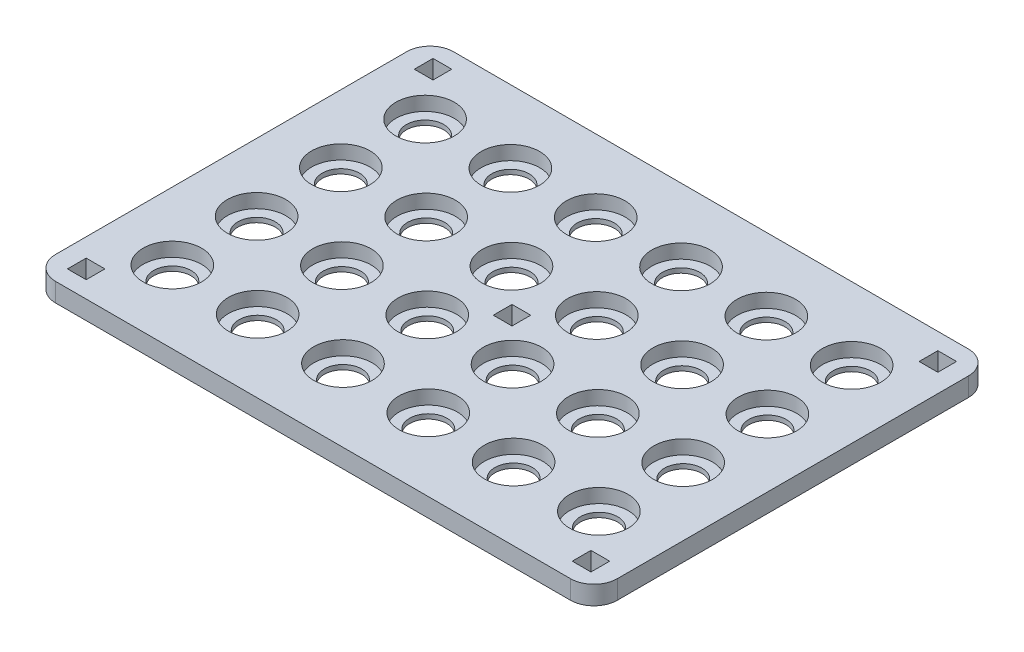
SolidWorks part; units mm, degrees
ref_plane "Front Plane" through (0, 0, 0) normal (0, 0, 1) x (1, 0, 0)
ref_plane "Top Plane" through (0, 0, 0) normal (0, 1, 0) x (1, 0, 0)
ref_plane "Right Plane" through (0, 0, 0) normal (1, 0, 0) x (0, 0, -1)
sketch "Sketch1" plane through (0, 0, 0) normal (0, 1, 0) x (1, 0, 0)
  line L1 (-60, 42.5) -> (60, 42.5)
  line L2 (-60, 42.5) -> (-60, -42.5)
  line L3 (-60, -42.5) -> (60, -42.5)
  line L4 (60, 42.5) -> (60, -42.5)
  line L5 (-60, 42.5) -> (60, -42.5) construction
  line L6 (-60, -42.5) -> (60, 42.5) construction
  point P0 (0, 0)
  dimension "D1" = 120
  dimension "D2" = 85
extrude "Boss-Extrude1" add sketch "Sketch1" along normal mid plane 35
sketch "Sketch2" plane through (0, 17.5, 0) normal (0, 1, 0) x (1, 0, 0)
  line L0 (-45.5658, 27) -> (-60, 27) construction
  line L1 (-60, 42.5) -> (-60, -42.5) construction
  line L2 (-45.5658, 27) -> (-45.5658, 42.5) construction
  line L3 (60, 42.5) -> (-60, 42.5) construction
  line L4 (45.5658, -27) -> (60, -27) construction
  line L5 (60, -42.5) -> (60, 42.5) construction
  line L6 (45.5658, -27) -> (45.5658, -42.5) construction
  line L7 (-60, -42.5) -> (60, -42.5) construction
  circle A0 centre (-45.5658, 27) radius 6.25
  circle A1 centre (-27.3395, 27) radius 6.25
  circle A2 centre (-9.1132, 27) radius 6.25
  circle A3 centre (9.1131, 27) radius 6.25
  circle A4 centre (27.3394, 27) radius 6.25
  circle A5 centre (45.5657, 27) radius 6.25
  circle A6 centre (-27.3395, 9) radius 6.25
  circle A7 centre (-9.1132, 9) radius 6.25
  circle A8 centre (9.1131, 9) radius 6.25
  circle A9 centre (27.3394, 9) radius 6.25
  circle A10 centre (45.5657, 9) radius 6.25
  circle A11 centre (-27.3394, -9) radius 6.25
  circle A12 centre (-9.1131, -9) radius 6.25
  circle A13 centre (9.1132, -9) radius 6.25
  circle A14 centre (27.3395, -9) radius 6.25
  circle A15 centre (45.5658, -9) radius 6.25
  circle A16 centre (-27.3394, -27) radius 6.25
  circle A17 centre (-9.1131, -27) radius 6.25
  circle A18 centre (9.1132, -27) radius 6.25
  circle A19 centre (27.3395, -27) radius 6.25
  circle A20 centre (45.5658, -27) radius 6.25
  circle A21 centre (-45.5658, 9) radius 6.25
  circle A22 centre (-45.5657, -9) radius 6.25
  circle A23 centre (-45.5657, -27) radius 6.25
  dimension "D3" = 12.5
  dimension "D4" = 18.2263
  dimension "D1" = 6
  dimension "D2" = 4
extrude "Cut-Extrude1" cut sketch "Sketch2" against normal blind 34
sketch "Sketch5" plane through (0, 17.5, 0) normal (0, 1, 0) x (1, 0, 0)
  circle A0 centre (-45.5658, 27) radius 4
  circle A1 centre (-27.3361, 27) radius 4
  circle A2 centre (-9.1064, 27) radius 4
  circle A3 centre (9.1233, 27) radius 4
  circle A4 centre (27.353, 27) radius 4
  circle A5 centre (45.5827, 27) radius 4
  circle A6 centre (-27.3361, 9) radius 4
  circle A7 centre (-9.1064, 9) radius 4
  circle A8 centre (9.1233, 9) radius 4
  circle A9 centre (27.353, 9) radius 4
  circle A10 centre (45.5827, 9) radius 4
  circle A11 centre (-27.3361, -9) radius 4
  circle A12 centre (-9.1064, -9) radius 4
  circle A13 centre (9.1233, -9) radius 4
  circle A14 centre (27.353, -9) radius 4
  circle A15 centre (45.5827, -9) radius 4
  circle A16 centre (-27.3361, -27) radius 4
  circle A17 centre (-9.1064, -27) radius 4
  circle A18 centre (9.1233, -27) radius 4
  circle A19 centre (27.353, -27) radius 4
  circle A20 centre (45.5827, -27) radius 4
  circle A21 centre (-45.5658, 9) radius 4
  circle A22 centre (-45.5657, -9) radius 4
  circle A23 centre (-45.5657, -27) radius 4
  dimension "D1" = 8
  dimension "D4" = 18.2297
  dimension "D2" = 6
  dimension "D3" = 4
extrude "Cut-Extrude4" cut sketch "Sketch5" against normal through all
fillet "Fillet1" radius 5 4 edges at (60, 0, -42.5) (60, 0, 42.5) (-60, 0, 42.5) (-60, 0, -42.5)
sketch "Sketch3" plane through (0, 0, -42.5) normal (0, 0, -1) x (-1, 0, 0)
  line L0 (-52.1057, 13.5) -> (-52.1057, 17.5) construction
  line L1 (52.1057, 13.5) -> (-52.1057, 13.5)
  line L2 (52.1057, 13.5) -> (52.1057, -13.5)
  line L3 (52.1057, -13.5) -> (-52.1057, -13.5)
  line L4 (-52.1057, 13.5) -> (-52.1057, -13.5)
  line L5 (-55, 17.5) -> (55, 17.5) construction
  line L6 (52.1057, -13.5) -> (52.1057, -17.5) construction
  line L7 (-55, -17.5) -> (55, -17.5) construction
  line L8 (-52.1057, 13.5) -> (-55, 13.5) construction
  line L11 (-55, 17.5) -> (-55, -17.5) construction
  line L13 (52.1057, -13.5) -> (55, -13.5) construction
  line L14 (55, -17.5) -> (55, 17.5) construction
  dimension "D1" = 27
extrude "Cut-Extrude2" cut sketch "Sketch3" against normal through all
sketch "Sketch4" plane through (60, 0, 0) normal (1, 0, 0) x (0, 0, -1)
  line L0 (-34.7795, 13.5) -> (-34.7795, 17.5) construction
  line L1 (34.7795, 13.5) -> (-34.7795, 13.5)
  line L2 (34.7795, 13.5) -> (34.7795, -13.5)
  line L3 (34.7795, -13.5) -> (-34.7795, -13.5)
  line L4 (-34.7795, 13.5) -> (-34.7795, -13.5)
  line L5 (-37.5, 17.5) -> (37.5, 17.5) construction
  line L6 (34.7795, 13.5) -> (37.5, 13.5) construction
  line L7 (-34.7795, 13.5) -> (-37.5, 13.5) construction
  line L8 (34.7795, -13.5) -> (34.7795, -17.5) construction
  line L9 (-37.5, -17.5) -> (37.5, -17.5) construction
  line L10 (34.7795, -13.5) -> (37.5, -13.5) construction
  line L11 (37.5, -17.5) -> (37.5, 17.5) construction
  line L12 (-37.5, 17.5) -> (-37.5, -17.5) construction
  dimension "D1" = 27
extrude "Cut-Extrude3" cut sketch "Sketch4" against normal through all
sketch "Sketch6" plane through (0, 17.5, 0) normal (0, 1, 0) x (1, 0, 0)
  line L1 (-2, 2) -> (2, 2)
  line L2 (-2, 2) -> (-2, -2)
  line L3 (-2, -2) -> (2, -2)
  line L4 (2, 2) -> (2, -2)
  line L5 (-2, 2) -> (2, -2) construction
  line L6 (-2, -2) -> (2, 2) construction
  point P0 (0, 0)
  dimension "D1" = 4
extrude "Boss-Extrude2" add sketch "Sketch6" against normal up to surface (35 mm away) up to face at (-45.5657, -17.5, 31)
chamfer "Chamfer1" distance 1 angle 45 8 edges at (0, -13.5, 2) (-2, -13.5, 0) (2, -13.5, 0) (0, -13.5, -2) (0, 13.5, 2) (-2, 13.5, 0) (2, 13.5, 0) (0, 13.5, -2)
sketch "Sketch7" plane through (0, 17.5, 0) normal (0, 1, 0) x (1, 0, 0)
  line L0 (-45.5658, 27) -> (-27.3361, 27) construction
  line L1 (-27.3361, 27) -> (-9.1064, 27) construction
  line L2 (-9.1064, 27) -> (9.1233, 27) construction
  line L3 (9.1233, 27) -> (27.353, 27) construction
  line L4 (27.353, 27) -> (45.5827, 27) construction
  line L5 (45.5827, 27) -> (45.5827, 9) construction
  line L6 (45.5827, 9) -> (45.5827, -9) construction
  line L7 (45.5827, -9) -> (45.5827, -27) construction
  line L8 (45.5827, -27) -> (27.353, -27) construction
  line L9 (27.353, -27) -> (9.1233, -27) construction
  line L10 (9.1233, -27) -> (-9.1064, -27) construction
  line L11 (-9.1064, -27) -> (-27.3361, -27) construction
  line L12 (-27.3361, -27) -> (-45.5657, -27) construction
  line L13 (-45.5657, -27) -> (-45.5657, -9) construction
  line L14 (-45.5657, -9) -> (-45.5658, 9) construction
  line L15 (-45.5658, 9) -> (-45.5658, 27) construction
  line L16 (-27.3361, 27) -> (-27.3361, 9) construction
  line L17 (-27.3361, 9) -> (-27.3361, -9) construction
  line L18 (-27.3361, -9) -> (-27.3361, -27) construction
  line L19 (-9.1064, 27) -> (-9.1064, 9) construction
  line L20 (-9.1064, 9) -> (-9.1064, -9) construction
  line L21 (-9.1064, -9) -> (-9.1064, -27) construction
  line L22 (9.1233, 27) -> (9.1233, 9) construction
  line L23 (9.1233, 9) -> (9.1233, -9) construction
  line L24 (9.1233, -9) -> (9.1233, -27) construction
  line L25 (27.353, 27) -> (27.353, 9) construction
  line L26 (27.353, 9) -> (27.353, -9) construction
  line L27 (27.353, -9) -> (27.353, -27) construction
  line L28 (-45.5658, 9) -> (-27.3361, 9) construction
  line L29 (-27.3361, 9) -> (-9.1064, 9) construction
  line L30 (-9.1064, 9) -> (9.1233, 9) construction
  line L31 (9.1233, 9) -> (27.353, 9) construction
  line L32 (27.353, 9) -> (45.5827, 9) construction
  line L33 (-45.5657, -9) -> (-27.3361, -9) construction
  line L34 (-27.3361, -9) -> (-9.1064, -9) construction
  line L35 (-9.1064, -9) -> (9.1233, -9) construction
  line L36 (9.1233, -9) -> (27.353, -9) construction
  line L37 (27.353, -9) -> (45.5827, -9) construction
  line L38 (-45.5657, -27) -> (-45.5657, -36) construction
  line L39 (-45.5657, -36) -> (45.5827, -36) construction
  line L40 (45.5827, -36) -> (45.5827, -27) construction
  text T0 "A1"
  text T1 "A2"
  text T2 "A3"
  text T3 "A4"
  text T4 "A5"
  text T5 "A6"
  text T6 "B1"
  text T7 "B2"
  text T8 "B3"
  text T9 "B4"
  text T10 "B5"
  text T11 "B6"
  text T12 "C1"
  text T13 "C2"
  text T14 "C3"
  text T15 "C4"
  text T16 "C5"
  text T17 "C6"
  text T18 "D1"
  text T19 "D2"
  text T20 "D3"
  text T21 "D4"
  text T22 "D5"
  text T23 "D6"
  point P24 (-28.1815, -36)
  point P26 (-9.388, -36)
  point P28 (9.4055, -36)
  point P31 (28.199, -36)
  point P64 (-45.5657, 18)
  point P65 (-36.4509, 27)
  point P66 (-27.3361, 18)
  point P67 (-18.2212, 27)
  point P68 (-9.1064, 18)
  point P69 (0.0085, 27)
  point P70 (9.1233, 18)
  point P71 (18.2382, 27)
  point P72 (36.4679, 27)
  point P73 (45.5827, 18)
  point P74 (27.353, 18)
  point P75 (-36.4509, 9)
  point P76 (-45.5657, 0)
  point P77 (-27.3361, 0)
  point P78 (-9.1064, 0)
  point P79 (9.1233, 0)
  point P80 (27.353, 0)
  point P81 (45.5827, 0)
  point P82 (36.4679, 9)
  point P83 (18.2382, 9)
  point P84 (0.0085, 9)
  point P85 (-18.2212, 9)
  point P86 (-36.4509, -9)
  point P87 (-36.4509, -27)
  point P88 (-18.2212, -27)
  point P89 (0.0085, -27)
  point P90 (18.2382, -27)
  point P91 (36.4679, -27)
  point P92 (36.4679, -9)
  point P93 (45.5827, -18)
  point P94 (27.353, -18)
  point P95 (9.1233, -18)
  point P96 (-9.1064, -18)
  point P97 (-27.3361, -18)
  point P98 (-45.5657, -18)
  dimension "D1" = 9
extrude "Cut-Extrude5" [suppressed] cut sketch "Sketch7" against normal blind 1
chamfer "Chamfer2" [suppressed] distance 1 angle 45
chamfer "Chamfer3" distance 1 angle 45 24 edges at (9.1131, 17.5, -20.75) (-45.5657, 17.5, 33.25) (-9.1131, 17.5, 33.25) (-27.3394, 17.5, 33.25) (27.3395, 17.5, 33.25) (9.1132, 17.5, 33.25) (45.5658, 17.5, 33.25) (45.5658, 17.5, 15.25) (27.3395, 17.5, 15.25) (9.1132, 17.5, 15.25) (-9.1131, 17.5, 15.25) (-27.3394, 17.5, 15.25) (-45.5657, 17.5, 15.25) (-45.5658, 17.5, -2.75) (-27.3395, 17.5, -2.75) (-9.1132, 17.5, -2.75) (9.1131, 17.5, -2.75) (27.3394, 17.5, -2.75) (45.5657, 17.5, -2.75) (45.5657, 17.5, -20.75) (27.3394, 17.5, -20.75) (-9.1132, 17.5, -20.75) (-27.3395, 17.5, -20.75) (-45.5658, 17.5, -20.75)
sketch "Sketch10" plane through (0, 0, 0) normal (0, 1, 0) x (1, 0, 0)
  line L1 (-64.9831, -48.4318) -> (62.395, -48.4318)
  line L2 (-64.9831, -48.4318) -> (-64.9831, 47.9662)
  line L3 (-64.9831, 47.9662) -> (62.395, 47.9662)
  line L4 (62.395, -48.4318) -> (62.395, 47.9662)
extrude "Cut-Extrude8" cut sketch "Sketch10" against normal up to surface (13.5 mm away) and the other way through all up to face at (0, -13.5, 0)
sketch "Sketch11" plane through (0, 17.5, 0) normal (0, 1, 0) x (1, 0, 0)
  line L0 (-56.0518, -38.9244) -> (-52.0518, -38.9244)
  line L1 (51.9482, -39.0756) -> (55.9482, -39.0756)
  line L2 (51.9482, -39.0756) -> (51.9482, -35.0756)
  line L3 (51.9482, -35.0756) -> (55.9482, -35.0756)
  line L4 (55.9482, -39.0756) -> (55.9482, -35.0756)
  line L5 (-56.0518, -38.9244) -> (-56.0518, -34.9244)
  line L6 (-56.0518, -34.9244) -> (-52.0518, -34.9244)
  line L7 (-52.0518, -38.9244) -> (-52.0518, -34.9244)
  line L8 (52.0518, 34.9244) -> (56.0518, 34.9244)
  line L9 (52.0518, 34.9244) -> (52.0518, 38.9244)
  line L10 (52.0518, 38.9244) -> (56.0518, 38.9244)
  line L11 (56.0518, 34.9244) -> (56.0518, 38.9244)
  line L12 (-55.9482, 35.0756) -> (-51.9482, 35.0756)
  line L13 (-55.9482, 35.0756) -> (-55.9482, 39.0756)
  line L14 (-55.9482, 39.0756) -> (-51.9482, 39.0756)
  line L15 (-51.9482, 35.0756) -> (-51.9482, 39.0756)
  line L16 (55.9482, -39.0756) -> (51.9482, -35.0756) construction
  line L17 (56.0518, 34.9244) -> (52.0518, 38.9244) construction
  line L18 (-51.9482, 35.0756) -> (-55.9482, 39.0756) construction
  line L19 (-52.0518, -38.9244) -> (-56.0518, -34.9244) construction
  line L20 (53.9482, -37.0756) -> (54.0518, 36.9244) construction
  line L21 (54.0518, 36.9244) -> (-53.9482, 37.0756) construction
  line L22 (-53.9482, 37.0756) -> (-54.0518, -36.9244) construction
  line L23 (-54.0518, -36.9244) -> (53.9482, -37.0756) construction
  line L24 (60, 0) -> (54.0001, 0) construction
  line L25 (60, -37.5) -> (60, 37.5) construction
  line L26 (-60, 0) -> (-54.0001, 0) construction
  line L27 (-60, 37.5) -> (-60, -37.5) construction
  line L28 (-0.0518, -37) -> (0, -42.5) construction
  line L29 (-55, -42.5) -> (55, -42.5) construction
  line L30 (0.0518, 37) -> (0, 42.5) construction
  line L31 (55, 42.5) -> (-55, 42.5) construction
  line L32 (54.0001, 0) -> (-54.0001, 0) construction
  line L33 (-2, -2) -> (2, -2)
  line L34 (-2, -2) -> (-2, 2)
  line L35 (-2, 2) -> (2, 2)
  line L36 (2, -2) -> (2, 2)
  line L37 (2, -2) -> (-2, 2) construction
  point P41 (0, 0)
  dimension "D1" = 4
  dimension "D2" = 4
  dimension "D3" = 4
  dimension "D4" = 4
  dimension "D5" = 108
  dimension "D6" = 74
extrude "Cut-Extrude9" cut sketch "Sketch11" against normal through all
